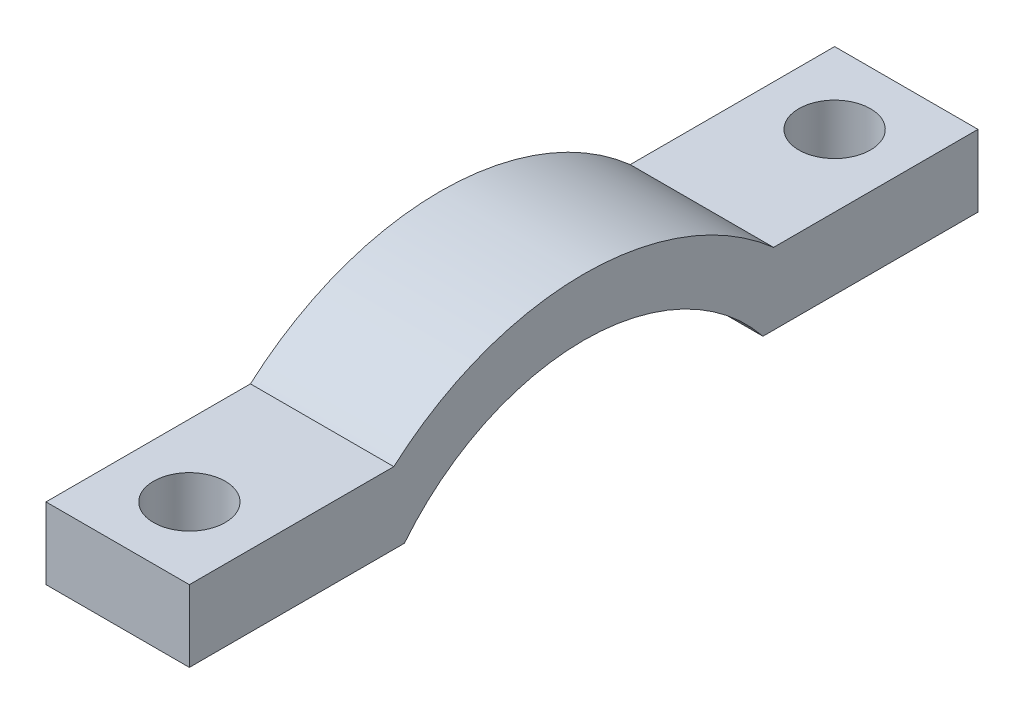
SolidWorks part; units mm, degrees
ref_plane "Plan de face" through (0, 0, 0) normal (0, 0, 1) x (1, 0, 0)
ref_plane "Plan de dessus" through (0, 0, 0) normal (0, 1, 0) x (1, 0, 0)
ref_plane "Plan de droite" through (0, 0, 0) normal (1, 0, 0) x (0, 0, -1)
sketch "Esquisse2" plane through (0, 0, 0) normal (1, 0, 0) x (0, 0, -1)
  line L0 (-16.7178, 10) -> (20.1552, 10) construction
  line L1 (-14.3614, 10) -> (-27.5028, 10)
  line L2 (-27.5028, 10) -> (-27.5028, 15)
  line L3 (-27.5028, 15) -> (-13.2439, 15)
  line L4 (14.3614, 10) -> (22.5028, 10)
  line L5 (27.5028, 15) -> (27.5028, 10)
  line L6 (27.5028, 15) -> (13.2439, 15)
  line L7 (27.5028, 10) -> (22.5028, 10)
  line L8 (-14.3614, 10) -> (-12.5028, 10)
  line L9 (12.5028, 10) -> (22.5028, 10)
  arc A0 (12.5028, 10) -> (-12.5028, 10) centre (0, 0) ccw
  arc A2 (13.2439, 15) -> (-13.2439, 15) centre (0, 0) ccw
  point P5 (-22.5028, 10)
  point P6 (22.5028, 10)
  point P7 (-12.5028, 10)
  point P8 (12.5028, 10)
  dimension "D1" = 32.02
  dimension "D3" = 10
  dimension "D5" = 5
  dimension "D7" = 4
  dimension "D2" = 10
  dimension "D4" = 10
  dimension "D6" = 5
  dimension "D8" = 5
  dimension "D9" = 5
extrude "BASE" add sketch "Esquisse2" along normal blind 10 contours L6 A2 L3 L2 L1 L8 A0 L9 L4 L7 L5
sketch "Esquisse5" plane through (0, 10, 0) normal (0, -1, 0) x (1, 0, 0)
  line L0 (5, 27.5028) -> (5, 12.5028) construction
  line L1 (10, 27.5028) -> (0, 27.5028) construction
  line L2 (10, 12.5028) -> (0, 12.5028) construction
  line L3 (-3.4429, 0) -> (13.3559, 0) construction
  circle A0 centre (5, 22.5028) radius 2.5
  circle A1 centre (5, -22.5028) radius 2.5
  dimension "D2" = 5
  dimension "D1" = 5
extrude "VIDE ACCES VIS" cut sketch "Esquisse5" against normal through all
